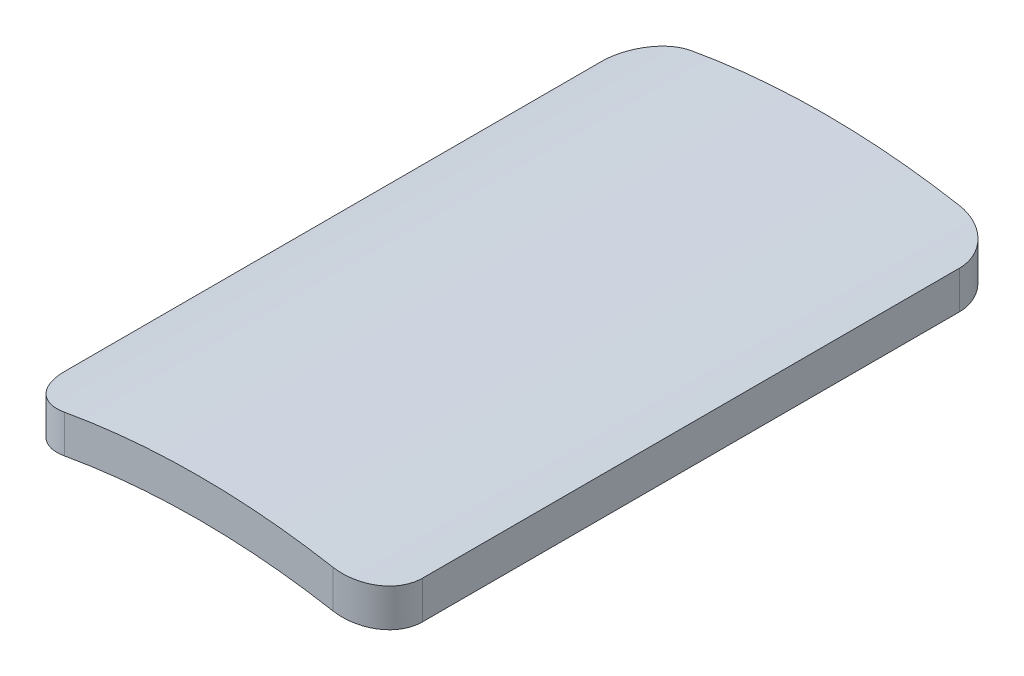
SolidWorks part; units mm, degrees
ref_plane "Front Plane" through (0, 0, 0) normal (0, 0, 1) x (1, 0, 0)
ref_plane "Top Plane" through (0, 0, 0) normal (0, 1, 0) x (1, 0, 0)
ref_plane "Right Plane" through (0, 0, 0) normal (1, 0, 0) x (0, 0, -1)
sketch "Sketch1" plane through (0, 0, 0) normal (0, 0, 1) x (1, 0, 0)
  line L0 (0, 180.6242) -> (0, -204.7074) construction
  line L1 (-60, 259.5117) -> (-60, 246.8117)
  line L2 (60, 259.5117) -> (60, 246.8117)
  line L4 (-60, 180.6242) -> (-60, -204.7074) construction
  line L5 (60, 180.6242) -> (60, -204.7074) construction
  arc A4 (60, 259.5117) -> (-60, 259.5117) centre (0, 12.7) ccw
  arc A5 (60, 246.8117) -> (-60, 246.8117) centre (0, 0) ccw
  point P4 (0, 254)
  point P11 (0, 266.7)
  dimension "D1" = 254
  dimension "D2" = 12.7
  dimension "D3" = 12.7
  dimension "D4" = 120
extrude "Boss-Extrude1" add sketch "Sketch1" along normal blind 210
fillet "Fillet2" radius 15 4 edges at (60, 253.1617, 0) (-60, 253.1617, 0) (-60, 253.1617, 210) (60, 253.1617, 210)
